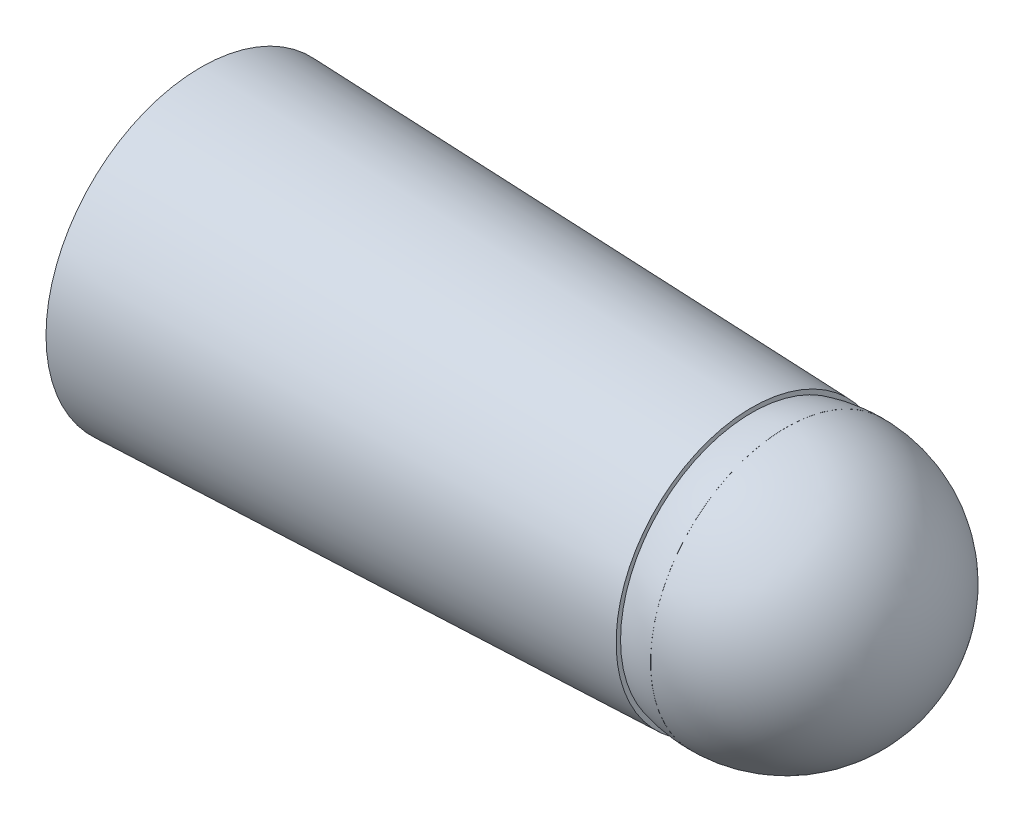
SolidWorks part; units mm, degrees
material "1060 Alloy"
ref_plane "Front Plane" through (0, 0, 0) normal (0, 0, 1) x (1, 0, 0)
ref_plane "Top Plane" through (0, 0, 0) normal (0, 1, 0) x (1, 0, 0)
ref_plane "Right Plane" through (0, 0, 0) normal (1, 0, 0) x (0, 0, -1)
sketch "Sketch1" plane through (0, 0, 0) normal (1, 0, 0) x (0, 0, -1)
  circle A0 centre (0, 0) radius 2.25
  dimension "D1" = 4.5
extrude "Boss-Extrude1" add sketch "Sketch1" along normal blind 8 draft 2
surface "Surface-Offset1" parameters "D1"=0.5
sketch "Sketch2" plane through (8.5, 0, 0) normal (1, 0, 0) x (0, 0, -1)
  line L0 (0, 1.9706) -> (0, -1.9706) construction
  line L1 (0, 1.9706) -> (0, -1.9706)
  arc A0 (0, -1.9706) -> (0, 1.9706) centre (0, 0) ccw
  circle A1 centre (0, 0) radius 1.9706 construction
  dimension "D1" = 1.9706
revolve "Revolve1" add sketch "Sketch2" angle 360 about L0
